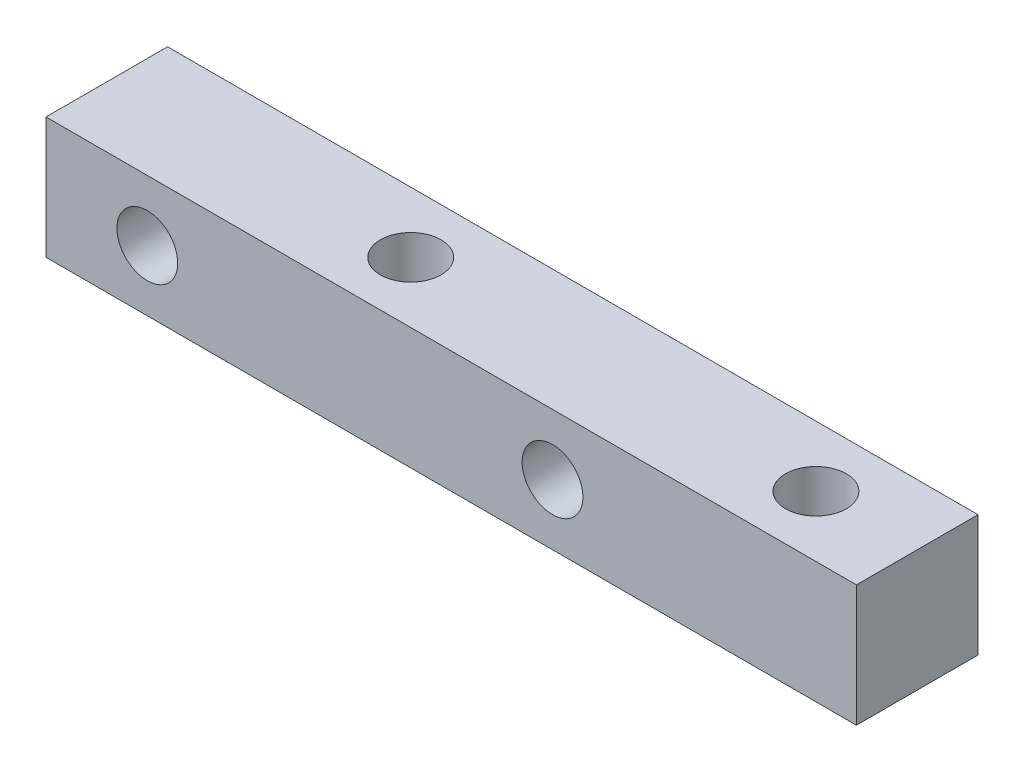
SolidWorks part; units mm, degrees
material "6061-T4 (SS)"
ref_plane "前视基准面" through (0, 0, 0) normal (0, 0, 1) x (1, 0, 0)
ref_plane "上视基准面" through (0, 0, 0) normal (0, 1, 0) x (1, 0, 0)
ref_plane "右视基准面" through (0, 0, 0) normal (1, 0, 0) x (0, 0, -1)
sketch "草图1" plane through (0, 0, 0) normal (0, 0, 1) x (1, 0, 0)
  line L0 (0, 3) -> (5, 3) construction
  line L1 (0, 0) -> (40, 0)
  line L2 (0, 0) -> (0, 6)
  line L3 (0, 6) -> (40, 6)
  line L4 (40, 0) -> (40, 6)
  line L5 (5, 3) -> (25, 3) construction
  circle A0 centre (5, 3) radius 1.5
  circle A1 centre (25, 3) radius 1.5
  dimension "D5" = 3
  dimension "D1" = 6
  dimension "D2" = 40
  dimension "D3" = 5
  dimension "D4" = 20
extrude "凸台-拉伸1" add sketch "草图1" along normal blind 6
sketch "草图2" plane through (0, 6, 0) normal (0, 1, 0) x (1, 0, 0)
  line L0 (40, -3) -> (35, -3) construction
  line L1 (40, -6) -> (40, 0) construction
  line L2 (35, -3) -> (15, -3) construction
  circle A0 centre (15, -3) radius 1.5
  circle A1 centre (35, -3) radius 1.5
  dimension "D3" = 3
  dimension "D1" = 5
  dimension "D2" = 20
extrude "切除-拉伸1" cut sketch "草图2" against normal blind 6
